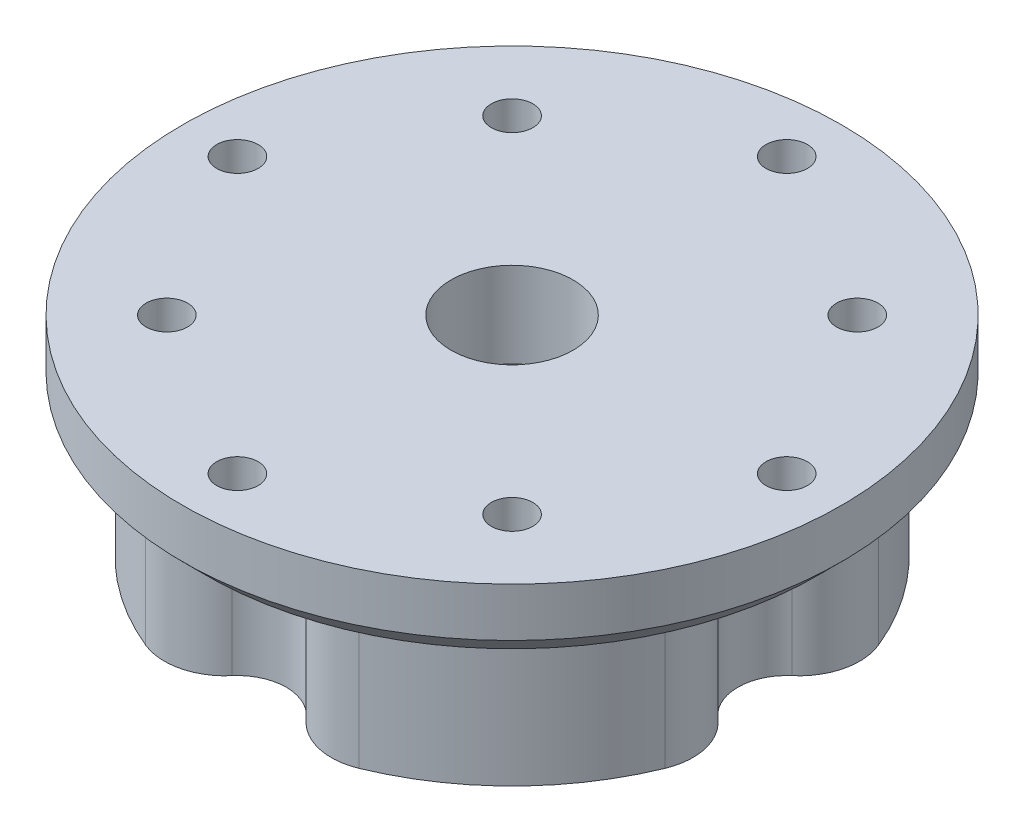
SolidWorks part; units mm, degrees
ref_plane "Front Plane" through (0, 0, 0) normal (0, 0, 1) x (1, 0, 0)
ref_plane "Top Plane" through (0, 0, 0) normal (0, 1, 0) x (1, 0, 0)
ref_plane "Right Plane" through (0, 0, 0) normal (1, 0, 0) x (0, 0, -1)
sketch "Sketch1" plane through (0, 0, 0) normal (0, 0, 1) x (1, 0, 0)
  line L0 (6.8, 0) -> (6.8, 4.953)
  line L1 (6.8, 4.953) -> (0, 4.953)
  line L2 (0, 4.953) -> (0, 17.156)
  line L5 (0, 17.156) -> (27, 17.156)
  line L7 (23, 0) -> (6.8, 0)
  line L10 (0, 0) -> (0, 16.4092) construction
  line L11 (23, 0) -> (23, 11.156)
  line L12 (23, 11.156) -> (27, 11.156)
  line L13 (27, 11.156) -> (27, 17.156)
  point P4 (0, 0)
  dimension "D1" = 6.8
  dimension "D2" = 27
  dimension "D3" = 4.953
  dimension "D4" = 46
  dimension "D5" = 6
  dimension "D6" = 17.156
revolve "Revolve1" add sketch "Sketch1" angle 360 about L10
sketch "Sketch2" plane through (0, 0, 0) normal (0, 1, 0) x (1, 0, 0)
  line L0 (0, 0) -> (-14.1421, 14.1421) construction
  line L2 (0, 0) -> (-22.5, 0) construction
  circle A0 centre (0, 0) radius 22.5 construction
  circle A1 centre (0, 0) radius 20 construction
  point P3 (-22.5, 0)
  point P8 (-14.1421, 14.1421)
  dimension "D1" = 45
  dimension "D3" = 40
  dimension "D2" = 45
hole_wizard "M3 Clearance Hole1" positions "Sketch2" profile "Sketch3" hole size "M3" standard "ANSI Metric" end condition through all
sketch "Sketch3" plane through (-14.1421, 0, -14.1421) normal (1, 0, 0) x (0, 0, -1)
  line L0 (0, 0) -> (0, 17.156)
  line L1 (0, 17.156) -> (1.7, 17.156)
  line L2 (1.7, 17.156) -> (1.7, 0)
  line L5 (1.7, 0) -> (0, 0)
  line L11 (0, -6.35) -> (0, 107.95) construction
  dimension "Thru Hole Dia." = 3.4
  dimension "Thru Hole Depth" = 17.156
sketch "Sketch5" plane through (0, 0, 0) normal (0, -1, 0) x (1, 0, 0)
  arc A0 (-22.9413, 1.6417) -> (-22.9413, -1.6417) centre (-22.5, 0) ccw construction
  arc A1 (-22.9413, 1.6417) -> (-22.9413, -1.6417) centre (-22.5, 0) ccw construction
  arc A2 (-22.65, -3.9972) -> (-22.65, 3.9972) centre (-22.5, 0) ccw
  arc A3 (-22.9413, -1.6417) -> (-22.9413, 1.6417) centre (0, 0) ccw construction
  arc A4 (-22.65, 3.9972) -> (-22.65, -3.9972) centre (0, 0) ccw
  dimension "D1" = 4
extrude "Cut-Extrude1" cut sketch "Sketch5" against normal up to surface (11.156 mm away) up to face at (-0.6, 11.156, 0)
fillet "Fillet1" radius 5 2 edges at (-22.65, 5.578, -3.9972) (-22.65, 5.578, 3.9972)
pattern_circular "CirPattern1" count 4 over 360 about axis through (0, 0, 0) along (0, 1, 0) of "M3 Clearance Hole1", "Cut-Extrude1", "Fillet1"
sketch "Sketch6" plane through (0, 17.156, 0) normal (0, 1, 0) x (1, 0, 0)
  point P0 (0, 0)
hole_wizard "CBORE for M5 SHCS1" positions "Sketch6" profile "Sketch7" counterbore size "M5" standard "ANSI Metric" end condition through all
sketch "Sketch7" plane through (0, 17.156, 0) normal (1, 0, 0) x (0, 0, 1)
  line L0 (0, 0) -> (0, 17.156)
  line L1 (0, 17.156) -> (2.75, 17.156)
  line L3 (2.75, 17.156) -> (2.75, 7)
  line L4 (2.75, 7) -> (5, 7)
  line L5 (5, 7) -> (5, 0)
  line L7 (5, 0) -> (0, 0)
  line L11 (0, -6.35) -> (0, 107.95) construction
  dimension "Thru Hole Dia." = 5.5
  dimension "Thru Hole Depth" = 17.156
  dimension "C'Bore Dia." = 10
  dimension "C'Bore Depth" = 7
chamfer "Chamfer1" distance 0.75 angle 45 1 edges at (0, 0, -6.8)
chamfer "Chamfer2" distance 2 angle 45 1 edges at (0, 11.156, -27)
